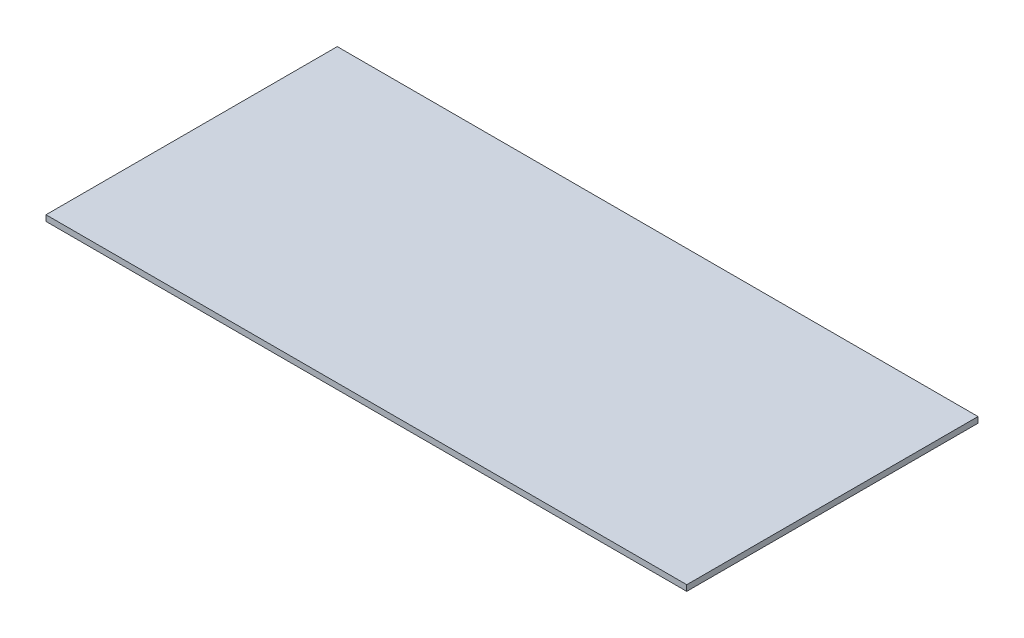
SolidWorks part; units mm, degrees
material "AISI 316 Stainless Steel Sheet (SS)"
ref_plane "Front Plane" through (0, 0, 0) normal (0, 0, 1) x (1, 0, 0)
ref_plane "Top Plane" through (0, 0, 0) normal (0, 1, 0) x (1, 0, 0)
ref_plane "Right Plane" through (0, 0, 0) normal (1, 0, 0) x (0, 0, -1)
sketch "Sketch1" plane through (0, 0, 0) normal (0, 1, 0) x (1, 0, 0)
  line L1 (0, 0) -> (330, 0)
  line L2 (0, 0) -> (0, 150)
  line L3 (0, 150) -> (330, 150)
  line L4 (330, 0) -> (330, 150)
  dimension "D1" = 150
  dimension "D2" = 330
extrude "Boss-Extrude1" add sketch "Sketch1" along normal blind 3
